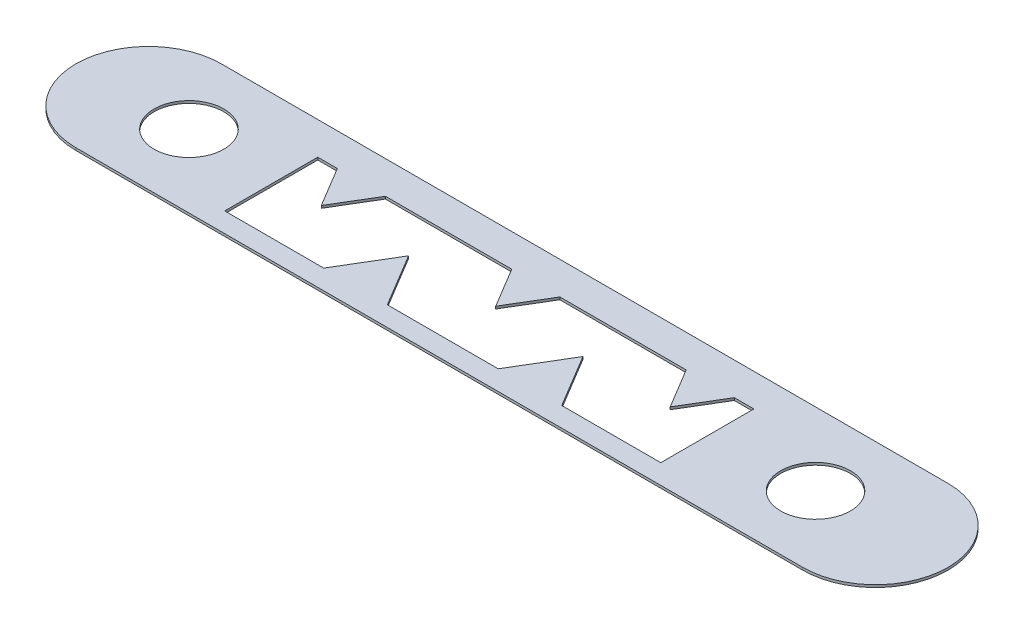
SolidWorks part; units mm, degrees
ref_plane "Front Plane" through (0, 0, 0) normal (0, 0, 1) x (1, 0, 0)
ref_plane "Top Plane" through (0, 0, 0) normal (0, 1, 0) x (1, 0, 0)
ref_plane "Right Plane" through (0, 0, 0) normal (1, 0, 0) x (0, 0, -1)
sketch "Sketch1" plane through (0, 0, 0) normal (0, 1, 0) x (1, 0, 0)
  line L0 (35.4167, 18.2292) -> (285.4167, 18.2292) construction
  line L1 (35.4167, 43.2292) -> (285.4167, 43.2292)
  line L2 (35.4167, -6.7708) -> (285.4167, -6.7708)
  line L3 (79.826, 43.2292) -> (79.826, -6.7708)
  line L4 (109.826, 32.0053) -> (109.826, 0)
  line L5 (139.826, 32.0053) -> (139.826, 0)
  line L6 (169.826, 32.0053) -> (169.826, 0)
  line L7 (199.826, 32.0053) -> (199.826, 0)
  line L8 (229.826, 43.2292) -> (229.826, -6.7708)
  line L9 (83.8885, 0) -> (103.0917, 32.0053)
  line L10 (86.5603, 32.0053) -> (105.7635, 0)
  line L11 (116.5603, 32.0053) -> (135.7635, 0)
  line L12 (133.0917, 32.0053) -> (113.8885, 0)
  line L13 (146.5603, 32.0053) -> (165.7635, 0)
  line L14 (163.0917, 32.0053) -> (143.8885, 0)
  line L15 (176.5603, 32.0053) -> (195.7635, 0)
  line L16 (193.0917, 32.0053) -> (173.8885, 0)
  line L17 (206.5603, 32.0053) -> (225.7635, 0)
  line L18 (223.0917, 32.0053) -> (203.8885, 0)
  line L19 (79.826, 32.0053) -> (229.826, 32.0053)
  line L20 (79.826, 0) -> (229.826, 0)
  line L21 (109.826, 43.2292) -> (109.826, -6.7708) construction
  line L22 (139.826, 43.2292) -> (139.826, -6.7708) construction
  line L23 (169.826, 43.2292) -> (169.826, -6.7708) construction
  line L24 (199.826, 43.2292) -> (199.826, -6.7708) construction
  arc A0 (35.4167, 43.2292) -> (35.4167, -6.7708) centre (35.4167, 18.2292) ccw
  arc A1 (285.4167, -6.7708) -> (285.4167, 43.2292) centre (285.4167, 18.2292) ccw
  circle A2 centre (49.2974, 18.2292) radius 12
  circle A3 centre (264.8255, 18.2292) radius 12
  point P2 (160.4167, 18.2292)
  point P7 (10.4167, 18.2292)
  point P8 (310.4167, 18.2292)
  dimension "D3" = 24
  dimension "D4" = 24
  dimension "D1" = 50
  dimension "D2" = 300
  dimension "D5" = 30
  dimension "D6" = 30
  dimension "D7" = 30
  dimension "D8" = 30
  dimension "D9" = 30
extrude "Boss-Extrude1" add sketch "Sketch1" along normal blind 0.85 contours L19 L10 L9 | L12 L20 L11 | L19 L13 L14 | L16 L20 L15 | L19 L17 L18 | L3 L19 L8 L1 | L20 L3 L2 L8 | L1 A0 L2 L3 A2 | L2 A1 L1 L8 A3
